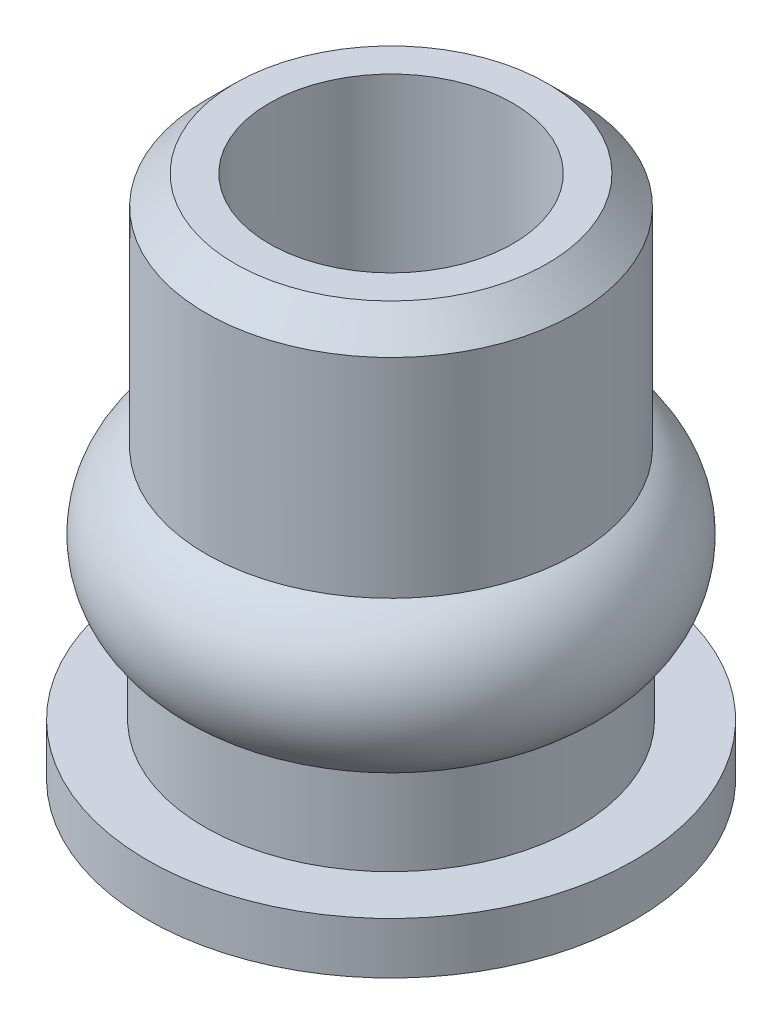
SolidWorks part; units mm, degrees
material "45"
ref_plane "前视基准面" through (0, 0, 0) normal (0, 0, 1) x (1, 0, 0)
ref_plane "上视基准面" through (0, 0, 0) normal (0, 1, 0) x (1, 0, 0)
ref_plane "右视基准面" through (0, 0, 0) normal (1, 0, 0) x (0, 0, -1)
sketch "草图1" plane through (0, 0, 0) normal (0, 0, 1) x (1, 0, 0)
  line L0 (0, 0) -> (0, 36.6) construction
  line L1 (0, 0) -> (8.5, 0)
  line L2 (8.5, 0) -> (8.5, 1.8)
  line L3 (8.5, 1.8) -> (6.5, 1.8)
  line L4 (6.5, 1.8) -> (6.5, 4.8)
  line L8 (6.45, 10.0244) -> (6.45, 18.3)
  line L9 (6.45, 18.3) -> (0, 18.3)
  line L10 (0, 18.3) -> (0, 0)
  arc A0 (6.5, 4.8) -> (6.45, 10.0244) centre (5, 7.3981) ccw
  point P9 (6.7065, 4.8)
  point P13 (0, 0)
  point P14 (7.5843, 8.3)
  point P15 (7.4367, 4.8)
  point P16 (6.4594, 8.3)
  point P17 (6.5521, 4.8)
  point P18 (6.5, 4.8)
  point P19 (6.45, 8.1103)
  dimension "D8" = 10
  dimension "D9" = 3
  dimension "D1" = 17
  dimension "D2" = 13
  dimension "D3" = 3
  dimension "D4" = 1.8
  dimension "D5" = 12.9
  dimension "D6" = 13.5
revolve "旋转1" add sketch "草图1" angle 360 about L0
hole_wizard "M10 螺纹孔1" positions "草图2" profile "草图3" tap size "M10" standard "GB"
sketch "草图2" plane through (0, 0, 0) normal (0, -1, 0) x (-1, 0, 0)
  point P0 (0, 0)
sketch "草图3" plane through (0, 0, 0) normal (1, 0, 0) x (0, 0, -1)
  line L0 (0, 0) -> (0, 27.0537)
  line L1 (0, 27.0537) -> (4.25, 24.5)
  line L2 (4.25, 24.5) -> (4.25, 0)
  line L5 (4.25, 0) -> (0, 0)
  line L10 (0, 27.0537) -> (-4.25, 24.5) construction
  line L11 (0, -6.35) -> (0, 107.95) construction
  dimension "螺纹孔钻头直径" = 8.5
  dimension "螺纹孔钻头深度" = 24.5
  dimension "导头角度" = 118
cosmetic thread "孔螺蚊线1" parameters "D1"=18.3, "D2"=10
chamfer "倒角1" distance 1 angle 45 1 edges at (6.45, 18.3, 0)
